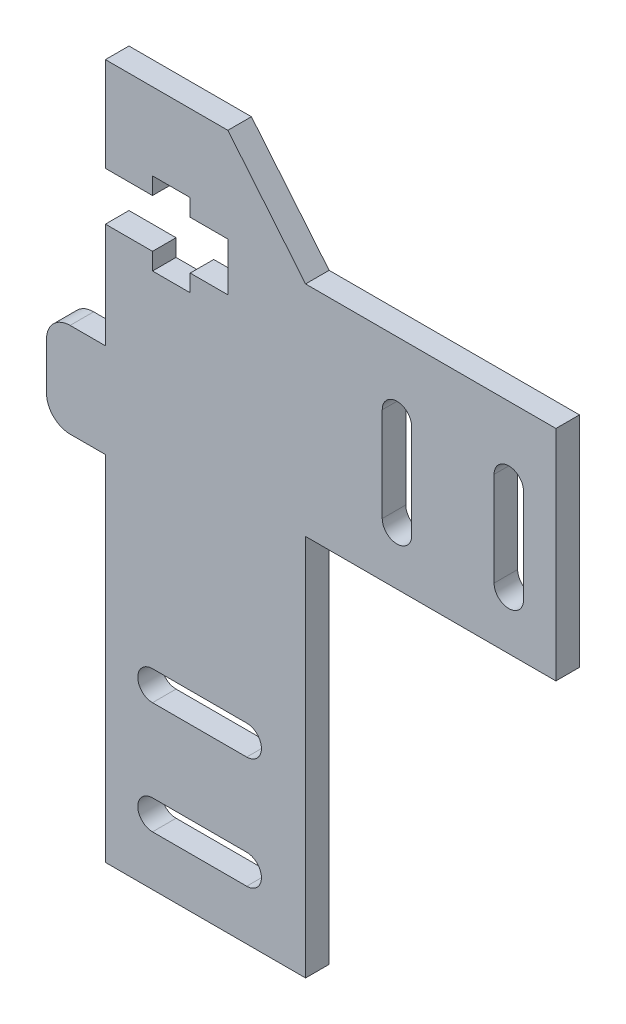
SolidWorks part; units mm, degrees
ref_plane "前视基准面" through (0, 0, 0) normal (0, 0, 1) x (1, 0, 0)
ref_plane "上视基准面" through (0, 0, 0) normal (0, 1, 0) x (1, 0, 0)
ref_plane "右视基准面" through (0, 0, 0) normal (1, 0, 0) x (0, 0, -1)
sketch "草图1" plane through (0, 0, 0) normal (0, 0, 1) x (1, 0, 0)
  line L0 (-8.3018, -11.7014) -> (-3.3018, -11.7014)
  line L1 (-8.3018, -11.7014) -> (-8.3018, -3.7014)
  line L2 (-8.3018, -3.7014) -> (-3.3018, -3.7014)
  line L3 (-3.3018, -3.7014) -> (-3.3018, 5.2486)
  line L4 (-3.3018, 5.2486) -> (0.6982, 5.2486)
  line L5 (0.6982, 5.2486) -> (0.6982, 3.7986)
  line L6 (0.6982, 3.7986) -> (3.8982, 3.7986)
  line L7 (3.8982, 3.7986) -> (3.8982, 5.2486)
  line L8 (3.8982, 5.2486) -> (7.0982, 5.2486)
  line L9 (7.0982, 5.2486) -> (7.0982, 9.3486)
  line L10 (7.0982, 9.3486) -> (3.8982, 9.3486)
  line L11 (3.8982, 9.3486) -> (3.8982, 10.7986)
  line L12 (3.8982, 10.7986) -> (0.6982, 10.7986)
  line L13 (0.6982, 10.7986) -> (0.6982, 9.3486)
  line L14 (0.6982, 9.3486) -> (-3.3018, 9.3486)
  line L15 (7.0982, 7.2986) -> (5.3982, 7.2986) construction
  line L16 (-8.3018, -7.7014) -> (-3.3018, -7.7014) construction
  line L17 (-3.3018, -11.7014) -> (-3.3018, -41.7014)
  line L18 (-3.3018, -41.7014) -> (13.6982, -41.7014)
  line L19 (13.6982, -41.7014) -> (13.6982, 17.3486) construction
  line L20 (13.6982, 17.3486) -> (-3.3018, 17.3486) construction
  line L21 (-3.3018, 17.3486) -> (-3.3018, 9.3486)
  line L22 (4.6982, -26.7014) -> (4.6982, -36.2014) construction
  line L23 (0.6982, -26.7014) -> (8.6982, -26.7014) construction
  line L24 (0.6982, -25.4514) -> (8.6982, -25.4514)
  line L25 (0.6982, -27.9514) -> (8.6982, -27.9514)
  line L26 (8.6982, -36.2014) -> (0.6982, -36.2014) construction
  line L27 (8.6982, -37.4514) -> (0.6982, -37.4514)
  line L28 (8.6982, -34.9514) -> (0.6982, -34.9514)
  line L29 (-3.3018, 17.3486) -> (7.0982, 17.3486)
  line L30 (7.0982, 17.3486) -> (13.6982, 9.3486)
  line L31 (13.6982, 9.3486) -> (34.959, 9.3486)
  line L32 (34.959, 9.3486) -> (34.959, -9.2232)
  line L33 (34.959, -9.2232) -> (13.6982, -9.2232)
  line L34 (13.6982, -9.2232) -> (13.6982, -41.7014)
  line L35 (30.959, -0.6514) -> (21.459, -0.6514) construction
  line L36 (30.959, 3.3486) -> (30.959, -4.6514) construction
  line L37 (32.209, 3.3486) -> (32.209, -4.6514)
  line L38 (29.709, 3.3486) -> (29.709, -4.6514)
  line L39 (21.459, 3.3486) -> (21.459, -4.6514) construction
  line L40 (22.709, 3.3486) -> (22.709, -4.6514)
  line L41 (20.209, 3.3486) -> (20.209, -4.6514)
  arc A0 (0.6982, -25.4514) -> (0.6982, -27.9514) centre (0.6982, -26.7014) ccw
  arc A1 (8.6982, -27.9514) -> (8.6982, -25.4514) centre (8.6982, -26.7014) ccw
  arc A2 (8.6982, -37.4514) -> (8.6982, -34.9514) centre (8.6982, -36.2014) ccw
  arc A3 (0.6982, -34.9514) -> (0.6982, -37.4514) centre (0.6982, -36.2014) ccw
  arc A4 (32.209, 3.3486) -> (29.709, 3.3486) centre (30.959, 3.3486) ccw
  arc A5 (29.709, -4.6514) -> (32.209, -4.6514) centre (30.959, -4.6514) ccw
  arc A6 (22.709, 3.3486) -> (20.209, 3.3486) centre (21.459, 3.3486) ccw
  arc A7 (20.209, -4.6514) -> (22.709, -4.6514) centre (21.459, -4.6514) ccw
  point P18 (2.2982, 3.7986)
  point P29 (4.6982, -26.7014)
  point P36 (4.6982, -36.2014)
  point P50 (30.959, -0.6514)
  point P57 (21.459, -0.6514)
  dimension "D9" = 30
  dimension "D14" = 4
  dimension "D1" = 3.2
  dimension "D2" = 4.1
  dimension "D3" = 5
  dimension "D4" = 8
  dimension "D5" = 7
  dimension "D6" = 15
  dimension "D7" = 9.5
  dimension "D8" = 8
  dimension "D10" = 34
  dimension "D11" = 17
  dimension "D12" = 8
  dimension "D13" = 9.5
  dimension "D15" = 10
extrude "凸台-拉伸1" add sketch "草图1" along normal blind 2
sketch "草图2" plane through (-3.3018, 0, 0) normal (-1, 0, 0) x (0, 0, 1)
  line L0 (1, 9.3486) -> (1, 5.2486) construction
  line L1 (2, 9.3486) -> (0, 9.3486) construction
  line L2 (2, 5.2486) -> (0, 5.2486) construction
  circle A0 centre (1, 7.2986) radius 2.05
sketch "草图4" plane through (0, 0, 2) normal (0, 0, 1) x (1, 0, 0)
  line L0 (0.6982, -36.2014) -> (8.6982, -36.2014)
  line L1 (0.6982, -26.7014) -> (8.6982, -26.7014)
  line L2 (30.959, 3.3486) -> (30.959, -4.6514)
  line L3 (21.459, 3.3486) -> (21.459, -4.6514)
fillet "圆角1" radius 2 2 edges at (-8.3018, -3.7014, 1) (-8.3018, -11.7014, 1)
